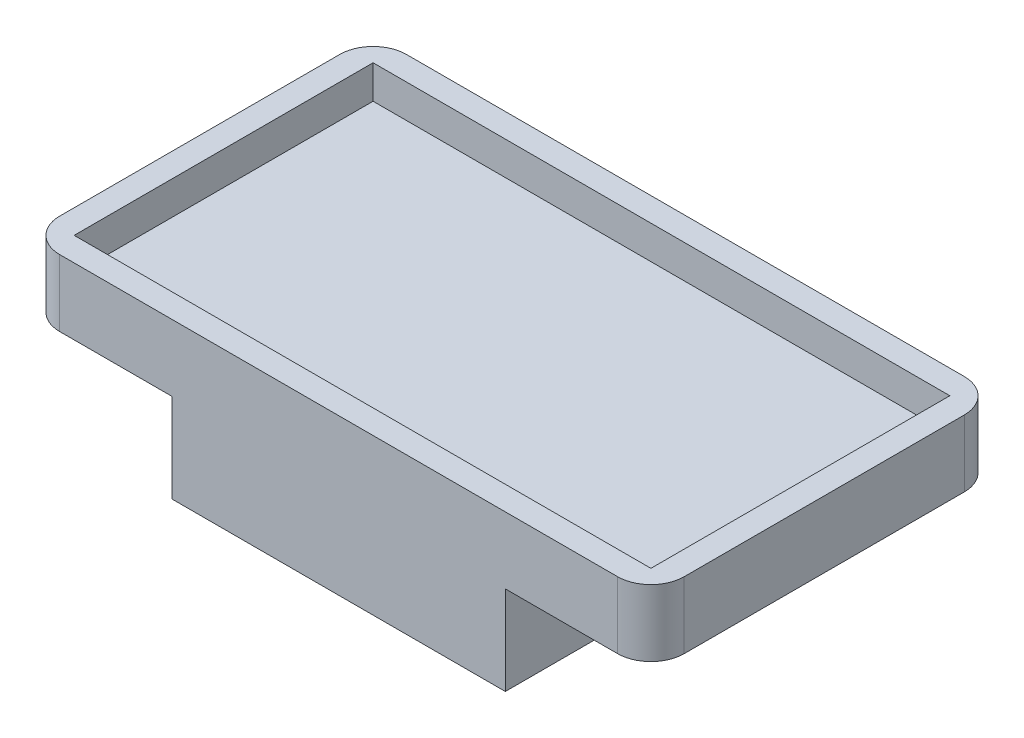
SolidWorks part; units mm, degrees
ref_plane "Alzado" through (0, 0, 0) normal (0, 0, 1) x (1, 0, 0)
ref_plane "Planta" through (0, 0, 0) normal (0, 1, 0) x (1, 0, 0)
ref_plane "Vista lateral" through (0, 0, 0) normal (1, 0, 0) x (0, 0, -1)
sketch "Croquis1" plane through (0, 0, 0) normal (0, 1, 0) x (1, 0, 0)
  line L1 (0, 0) -> (50.2, 0) construction
  line L2 (0, 0) -> (0, 25.2) construction
  line L3 (0, 25.2) -> (50.2, 25.2) construction
  line L4 (50.2, 0) -> (50.2, 25.2) construction
  line L5 (-3, 28.2) -> (53.2, 28.2)
  line L6 (-3, 28.2) -> (-3, -3)
  line L7 (-3, -3) -> (53.2, -3)
  line L8 (53.2, 28.2) -> (53.2, -3)
  point P10 (25.1, 28.2)
  point P11 (25.1, 25.2)
  point P12 (50.2, 12.6)
  point P13 (53.2, 12.6)
  dimension "D1" = 50.2
  dimension "D2" = 25.2
  dimension "D3" = 3
  dimension "D4" = 3
extrude "Saliente-Extruir1" add sketch "Croquis1" along normal blind 6
sketch "Croquis2" plane through (0, 6, 0) normal (0, 1, 0) x (1, 0, 0)
  line L1 (0, 0) -> (50.2, 0) construction
  line L2 (0, 0) -> (0, 25.2) construction
  line L3 (0, 25.2) -> (50.2, 25.2) construction
  line L4 (50.2, 0) -> (50.2, 25.2) construction
  dimension "D1" = 50.2
  dimension "D2" = 25.2
sketch "Croquis3" plane through (0, 6, 0) normal (0, 1, 0) x (1, 0, 0)
  line L0 (50.2, 0) -> (50.2, 25.2) construction
  line L1 (-0.85, 26.05) -> (51.05, 26.05)
  line L2 (-0.85, 26.05) -> (-0.85, -0.85)
  line L3 (-0.85, -0.85) -> (51.05, -0.85)
  line L4 (51.05, 26.05) -> (51.05, -0.85)
  line L5 (53.2, 28.2) -> (-3, 28.2) construction
  line L6 (-3, 28.2) -> (-3, -3) construction
  line L7 (0, 0) -> (50.2, 0) construction
  point P8 (25.1, 28.2)
  point P9 (25.1, 26.05)
  point P12 (-3, 12.6)
  point P13 (-0.85, 12.6)
  dimension "D1" = 0.85
  dimension "D2" = 0.85
extrude "Cortar-Extruir1" cut sketch "Croquis3" against normal blind 3
sketch "Croquis5" plane through (0, 0, 0) normal (0, -1, 0) x (1, 0, 0)
  line L0 (53.2, 3) -> (53.2, -28.2) construction
  line L1 (-3, 3) -> (53.2, 3)
  line L2 (-3, 3) -> (-3, -15)
  line L3 (-3, -15) -> (53.2, -15)
  line L4 (53.2, 3) -> (53.2, -15)
  dimension "D1" = 18
extrude "Saliente-Extruir2" add sketch "Croquis5" along normal blind 8
sketch "Croquis6" plane through (-3, 0, 0) normal (-1, 0, 0) x (0, 0, 1)
  line L0 (3, 6) -> (3, -8) construction
  line L1 (-15, 0) -> (-1.7, 0)
  line L2 (-15, 0) -> (-15, -3.9)
  line L3 (-15, -3.9) -> (-1.7, -3.9)
  line L4 (-1.7, 0) -> (-1.7, -3.9)
  dimension "D1" = 3.9
  dimension "D2" = 4.7
extrude "Cortar-Extruir2" cut sketch "Croquis6" against normal through all
sketch "Croquis7" plane through (0, 0, -15) normal (0, 0, -1) x (-1, 0, 0)
  line L0 (-25.1, -8) -> (-25.1, 6) construction
  line L1 (3, -8) -> (-53.2, -8) construction
  line L2 (0, 6) -> (-50.2, 6) construction
  line L3 (-53.2, 0) -> (3, 0) construction
  line L4 (-53.2, -8) -> (-40.1, -8)
  line L5 (-53.2, -8) -> (-53.2, 0)
  line L6 (-53.2, 0) -> (-40.1, 0)
  line L7 (-40.1, -8) -> (-40.1, 0)
  line L8 (3, 0) -> (-10.1, 0)
  line L9 (-10.1, -8) -> (-10.1, 0)
  line L10 (3, -8) -> (-10.1, -8)
  line L11 (3, -8) -> (3, 0)
  dimension "D1" = 15
extrude "Cortar-Extruir3" cut sketch "Croquis7" against normal through all
fillet "Redondeo3" radius 3 4 edges at (53.2, 3, -28.2) (-3, 3, 3) (-3, 3, -28.2) (53.2, 3, 3)
sketch "Croquis4" plane through (0, 0, 0) normal (0, -1, 0) x (1, 0, 0)
  line L0 (-3, -12.6) -> (53.2, -12.6) construction
  line L1 (-3, -25.2) -> (-3, 0) construction
  line L2 (53.2, 0) -> (53.2, -25.2) construction
